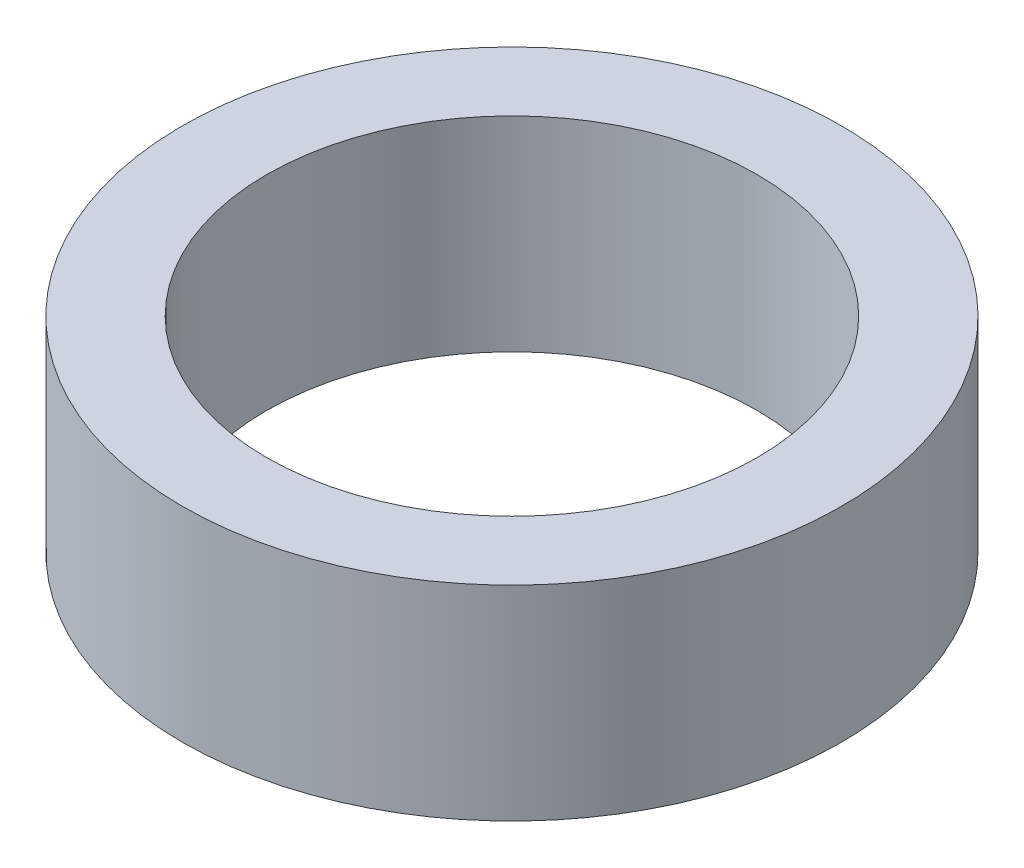
SolidWorks part; units mm, degrees
ref_plane "Front Plane" through (0, 0, 0) normal (0, 0, 1) x (1, 0, 0)
ref_plane "Top Plane" through (0, 0, 0) normal (0, 1, 0) x (1, 0, 0)
ref_plane "Right Plane" through (0, 0, 0) normal (1, 0, 0) x (0, 0, -1)
sketch "Sketch1" plane through (0, 0, 0) normal (0, 1, 0) x (1, 0, 0)
  circle A1 centre (0, 0) radius 9.4488
  circle A2 centre (0, 0) radius 12.7
  dimension "D1" = 25.4
  dimension "D2" = 18.8976
extrude "Boss-Extrude1" add sketch "Sketch1" along normal blind 7.874
